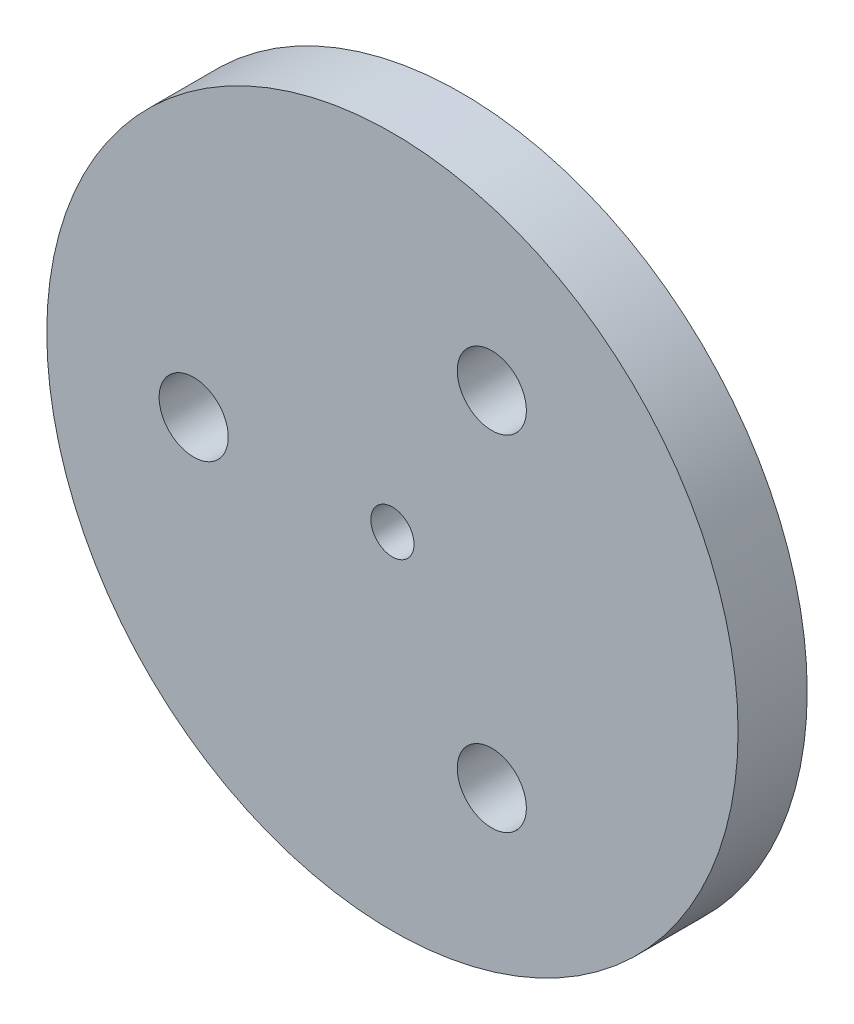
SolidWorks part; units mm, degrees
ref_plane "Ebene vorne" through (0, 0, 0) normal (0, 0, 1) x (1, 0, 0)
ref_plane "Ebene oben" through (0, 0, 0) normal (0, 1, 0) x (1, 0, 0)
ref_plane "Ebene rechts" through (0, 0, 0) normal (1, 0, 0) x (0, 0, -1)
sketch "Skizze1" plane through (0, 0, 0) normal (0, 0, 1) x (1, 0, 0)
  line L0 (0, 0) -> (-11.5, 0) construction
  circle A0 centre (0, 0) radius 20
  circle A1 centre (-11.5, 0) radius 2
  circle A2 centre (5.75, 9.9593) radius 2
  circle A3 centre (5.75, -9.9593) radius 2
  point P11 (0, 0)
  dimension "D2" = 40
  dimension "D3" = 4
  dimension "D1" = 11.5
  dimension "D4" = 3
extrude "Aufsatz-Linear austragen1" add sketch "Skizze1" along normal blind 4
sketch "Skizze2" plane through (0, 0, 4) normal (0, 0, 1) x (1, 0, 0)
  circle A0 centre (0, 0) radius 1.25
  dimension "D1" = 2.5
extrude "Schnitt-Linear austragen1" cut sketch "Skizze2" against normal through all
